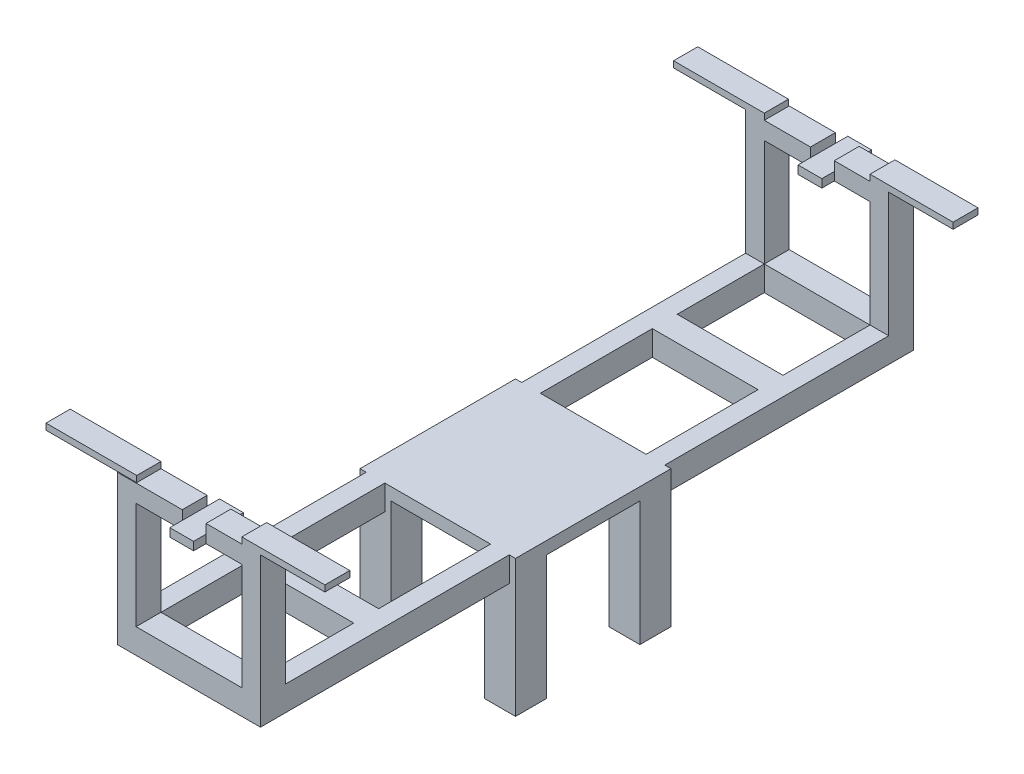
SolidWorks part; units mm, degrees
ref_plane "前视基准面" through (0, 0, 0) normal (0, 0, 1) x (1, 0, 0)
ref_plane "上视基准面" through (0, 0, 0) normal (0, 1, 0) x (1, 0, 0)
ref_plane "右视基准面" through (0, 0, 0) normal (1, 0, 0) x (0, 0, -1)
sketch "草图1" plane through (0, 0, 0) normal (0, 1, 0) x (1, 0, 0)
  line L1 (-12.5, -12.5) -> (12.5, -12.5)
  line L2 (-12.5, -12.5) -> (-12.5, 12.5)
  line L3 (-12.5, 12.5) -> (12.5, 12.5)
  line L4 (12.5, -12.5) -> (12.5, 12.5)
  line L5 (-12.5, -12.5) -> (12.5, 12.5) construction
  line L6 (-12.5, 12.5) -> (12.5, -12.5) construction
  point P0 (0, 0)
  dimension "D1" = 25
  dimension "D2" = 25
extrude "凸台-拉伸1" add sketch "草图1" along normal blind 100
pattern_linear "阵列(线性)1" count 2 spacing 100 along (0, 0, 1) count 2 spacing 100 along (1, 0, 0) of "凸台-拉伸1"
sketch "草图2" plane through (0, 100, 0) normal (0, 1, 0) x (1, 0, 0)
  line L0 (12.5, 12.5) -> (-12.5, 12.5) construction
  line L1 (-12.5, -112.5) -> (112.5, -112.5)
  line L2 (-12.5, -112.5) -> (-12.5, 12.5)
  line L3 (-12.5, 12.5) -> (112.5, 12.5)
  line L4 (112.5, -112.5) -> (112.5, 12.5)
  line L5 (-12.5, -112.5) -> (112.5, 12.5) construction
  line L6 (-12.5, 12.5) -> (112.5, -112.5) construction
  line L7 (87.5, -112.5) -> (112.5, -112.5) construction
  line L8 (112.5, -112.5) -> (112.5, -87.5) construction
  line L9 (-12.5, -87.5) -> (-12.5, -112.5) construction
  point P0 (50, -50)
  dimension "D1" = 0
  dimension "D2" = 0
  dimension "D3" = 0
  dimension "D4" = 0
extrude "凸台-拉伸2" add sketch "草图2" along normal blind 10
sketch "草图3" plane through (0, 0, 112.5) normal (0, 0, 1) x (1, 0, 0)
  line L0 (-12.5, 110) -> (112.5, 110) construction
  line L1 (-7.5, 90) -> (7.5, 90)
  line L2 (-7.5, 90) -> (-7.5, 110)
  line L3 (-7.5, 110) -> (7.5, 110)
  line L4 (7.5, 90) -> (7.5, 110)
  line L5 (-7.5, 90) -> (7.5, 110) construction
  line L6 (-7.5, 110) -> (7.5, 90) construction
  line L7 (-12.5, 110) -> (-12.5, 0) construction
  line L8 (92.5, 90) -> (107.5, 90)
  line L9 (92.5, 90) -> (92.5, 110)
  line L10 (92.5, 110) -> (107.5, 110)
  line L11 (107.5, 90) -> (107.5, 110)
  line L12 (92.5, 90) -> (107.5, 110) construction
  line L13 (92.5, 110) -> (107.5, 90) construction
  line L14 (87.5, 100) -> (87.5, 0) construction
  point P0 (0, 100)
  point P7 (100, 100)
  dimension "D1" = 20
  dimension "D2" = 20
  dimension "D3" = 15
  dimension "D4" = 15
  dimension "D5" = 5
  dimension "D6" = 5
extrude "凸台-拉伸3" add sketch "草图3" along normal blind 200
sketch "草图4" plane through (7.5, 0, 0) normal (1, 0, 0) x (0, 0, -1)
  line L0 (-312.5, 110) -> (-112.5, 110) construction
  line L1 (-222.5, 110) -> (-202.5, 110)
  line L2 (-222.5, 110) -> (-222.5, 90)
  line L3 (-222.5, 90) -> (-202.5, 90)
  line L4 (-202.5, 110) -> (-202.5, 90)
  line L5 (-312.5, 90) -> (-112.5, 90) construction
  line L6 (-112.5, 90) -> (-112.5, 110) construction
  line L7 (-112.5, 110) -> (-112.5, 0) construction
  dimension "D1" = 90
  dimension "D2" = 110
extrude "凸台-拉伸4" add sketch "草图4" along normal up to next
pattern_linear "阵列(线性)2" count 2 spacing 90 along (0, 0, 1) of "凸台-拉伸4"
sketch "草图5" plane through (0, 110, 0) normal (0, 1, 0) x (1, 0, 0)
  line L1 (107.5, -312.5) -> (92.5, -312.5)
  line L2 (107.5, -312.5) -> (107.5, -292.5)
  line L3 (107.5, -292.5) -> (92.5, -292.5)
  line L4 (92.5, -312.5) -> (92.5, -292.5)
  line L5 (-7.5, -312.5) -> (7.5, -312.5)
  line L6 (-7.5, -312.5) -> (-7.5, -292.5)
  line L7 (-7.5, -292.5) -> (7.5, -292.5)
  line L8 (7.5, -312.5) -> (7.5, -292.5)
extrude "凸台-拉伸5" add sketch "草图5" along normal blind 100
sketch "草图6" plane through (7.5, 0, 0) normal (1, 0, 0) x (0, 0, -1)
  line L0 (-312.5, 90) -> (-312.5, 210) construction
  line L1 (-312.5, 195.8962) -> (-292.5, 195.8962)
  line L2 (-312.5, 195.8962) -> (-312.5, 210)
  line L3 (-312.5, 210) -> (-292.5, 210)
  line L4 (-292.5, 195.8962) -> (-292.5, 210)
extrude "凸台-拉伸6" add sketch "草图6" along normal up to next
sketch "草图7" plane through (0, 0, 292.5) normal (0, 0, -1) x (-1, 0, 0)
  line L0 (-107.5, 210) -> (7.5, 210) construction
  line L1 (-63.7441, 210) -> (-44.6365, 210)
  line L2 (-63.7441, 210) -> (-63.7441, 202.5136)
  line L3 (-63.7441, 202.5136) -> (-44.6365, 202.5136)
  line L4 (-44.6365, 210) -> (-44.6365, 202.5136)
extrude "切除-拉伸1" cut sketch "草图7" against normal up to next
sketch "草图8" plane through (0, 210, 0) normal (0, 1, 0) x (1, 0, 0)
  line L1 (7.5, -292.5) -> (-65.4385, -292.5)
  line L2 (7.5, -292.5) -> (7.5, -311.9548)
  line L3 (7.5, -311.9548) -> (-65.4385, -311.9548)
  line L4 (-65.4385, -292.5) -> (-65.4385, -311.9548)
extrude "凸台-拉伸7" add sketch "草图8" along normal blind 5
sketch "草图9" plane through (0, 210, 0) normal (0, 1, 0) x (1, 0, 0)
  line L1 (92.5, -292.5) -> (159.2888, -292.5)
  line L2 (92.5, -292.5) -> (92.5, -312.5)
  line L3 (92.5, -312.5) -> (159.2888, -312.5)
  line L4 (159.2888, -292.5) -> (159.2888, -312.5)
extrude "凸台-拉伸8" add sketch "草图9" along normal blind 5
ref_plane "基准面4" through (0, 0, 50) normal (0, 0, 1) x (1, 0, 0)
mirror "镜向1" about plane through (0, 0, 50) normal (0, 0, 1) of "凸台-拉伸7", "凸台-拉伸8", "切除-拉伸1", "凸台-拉伸6", "凸台-拉伸5", "阵列(线性)2", "凸台-拉伸4", "凸台-拉伸3"
sketch "草图10" plane through (0, 0, 312.5) normal (0, 0, 1) x (1, 0, 0)
  line L0 (44.6365, 202.5136) -> (44.6365, 195.8962)
  line L1 (92.5, 195.8962) -> (7.5, 195.8962) construction
  line L2 (44.6365, 195.8962) -> (63.7441, 195.8962)
  line L3 (63.7441, 195.8962) -> (63.7441, 202.5136)
  line L4 (63.7441, 202.5136) -> (44.6365, 202.5136)
extrude "凸台-拉伸9" add sketch "草图10" along normal blind 10 and the other way blind 30
sketch "草图11" plane through (0, 0, -192.5) normal (0, 0, 1) x (1, 0, 0)
  line L0 (44.6365, 202.5136) -> (44.6365, 195.8962)
  line L1 (44.6365, 195.8962) -> (63.7441, 195.8962)
  line L2 (63.7441, 195.8962) -> (63.7441, 202.5136)
  line L3 (63.7441, 202.5136) -> (44.6365, 202.5136)
extrude "凸台-拉伸10" add sketch "草图11" along normal blind 10 and the other way blind 30
